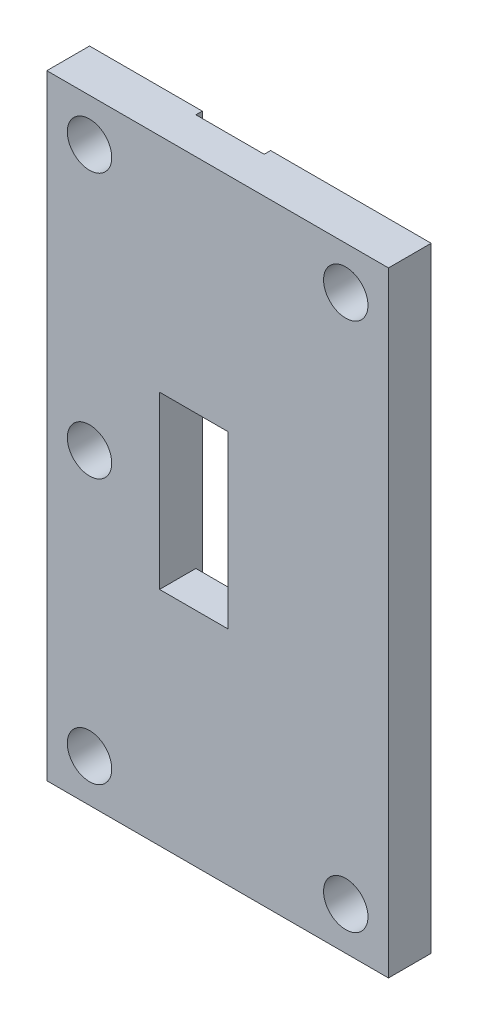
SolidWorks part; units mm, degrees
ref_plane "Front Plane" through (0, 0, 0) normal (0, 0, 1) x (1, 0, 0)
ref_plane "Top Plane" through (0, 0, 0) normal (0, 1, 0) x (1, 0, 0)
ref_plane "Right Plane" through (0, 0, 0) normal (1, 0, 0) x (0, 0, -1)
sketch "Sketch1" plane through (0, 0, 0) normal (0, 1, 0) x (1, 0, 0)
  line L1 (0, 0) -> (40, 0)
  line L2 (0, 0) -> (0, 5)
  line L3 (0, 5) -> (40, 5)
  line L4 (40, 0) -> (40, 5)
  dimension "D1" = 40
  dimension "D2" = 5
  dimension "D3" = 0
extrude "Boss-Extrude1" add sketch "Sketch1" along normal blind 72
sketch "Sketch2" plane through (0, 0, -5) normal (0, 0, -1) x (-1, 0, 0)
  line L0 (-40, 72) -> (0, 72) construction
  line L1 (-13.2, 72) -> (-21.2, 72)
  line L2 (-13.2, 72) -> (-13.2, 0)
  line L3 (-13.2, 0) -> (-21.2, 0)
  line L4 (-21.2, 72) -> (-21.2, 0)
  line L5 (-40, 0) -> (0, 0) construction
  line L7 (-40, 72) -> (-40, 0) construction
  dimension "D1" = 8
  dimension "D2" = 18.8
extrude "Cut-Extrude1" cut sketch "Sketch2" against normal blind 0.75
sketch "Sketch3" plane through (13.2, 0, 0) normal (1, 0, 0) x (0, 0, -1)
  line L1 (4.25, 71.4) -> (4.85, 71.4)
  line L2 (4.25, 71.4) -> (4.25, 70.8)
  line L3 (4.25, 70.8) -> (4.85, 70.8)
  line L4 (4.85, 71.4) -> (4.85, 70.8)
  line L5 (4.25, 69.4) -> (4.85, 69.4)
  line L6 (4.25, 69.4) -> (4.25, 68.8)
  line L7 (4.25, 68.8) -> (4.85, 68.8)
  line L8 (4.85, 69.4) -> (4.85, 68.8)
  line L9 (4.25, 67.4) -> (4.85, 67.4)
  line L10 (4.25, 67.4) -> (4.25, 66.8)
  line L11 (4.25, 66.8) -> (4.85, 66.8)
  line L12 (4.85, 67.4) -> (4.85, 66.8)
  line L13 (4.25, 65.4) -> (4.85, 65.4)
  line L14 (4.25, 65.4) -> (4.25, 64.8)
  line L15 (4.25, 64.8) -> (4.85, 64.8)
  line L16 (4.85, 65.4) -> (4.85, 64.8)
  line L17 (4.25, 63.4) -> (4.85, 63.4)
  line L18 (4.25, 63.4) -> (4.25, 62.8)
  line L19 (4.25, 62.8) -> (4.85, 62.8)
  line L20 (4.85, 63.4) -> (4.85, 62.8)
  line L21 (4.25, 61.4) -> (4.85, 61.4)
  line L22 (4.25, 61.4) -> (4.25, 60.8)
  line L23 (4.25, 60.8) -> (4.85, 60.8)
  line L24 (4.85, 61.4) -> (4.85, 60.8)
  line L25 (4.25, 59.4) -> (4.85, 59.4)
  line L26 (4.25, 59.4) -> (4.25, 58.8)
  line L27 (4.25, 58.8) -> (4.85, 58.8)
  line L28 (4.85, 59.4) -> (4.85, 58.8)
  line L29 (4.25, 57.4) -> (4.85, 57.4)
  line L30 (4.25, 57.4) -> (4.25, 56.8)
  line L31 (4.25, 56.8) -> (4.85, 56.8)
  line L32 (4.85, 57.4) -> (4.85, 56.8)
  line L33 (4.25, 55.4) -> (4.85, 55.4)
  line L34 (4.25, 55.4) -> (4.25, 54.8)
  line L35 (4.25, 54.8) -> (4.85, 54.8)
  line L36 (4.85, 55.4) -> (4.85, 54.8)
  line L37 (4.25, 53.4) -> (4.85, 53.4)
  line L38 (4.25, 53.4) -> (4.25, 52.8)
  line L39 (4.25, 52.8) -> (4.85, 52.8)
  line L40 (4.85, 53.4) -> (4.85, 52.8)
  line L41 (4.25, 51.4) -> (4.85, 51.4)
  line L42 (4.25, 51.4) -> (4.25, 50.8)
  line L43 (4.25, 50.8) -> (4.85, 50.8)
  line L44 (4.85, 51.4) -> (4.85, 50.8)
  line L45 (4.25, 49.4) -> (4.85, 49.4)
  line L46 (4.25, 49.4) -> (4.25, 48.8)
  line L47 (4.25, 48.8) -> (4.85, 48.8)
  line L48 (4.85, 49.4) -> (4.85, 48.8)
  line L49 (4.25, 47.4) -> (4.85, 47.4)
  line L50 (4.25, 47.4) -> (4.25, 46.8)
  line L51 (4.25, 46.8) -> (4.85, 46.8)
  line L52 (4.85, 47.4) -> (4.85, 46.8)
  line L53 (4.25, 45.4) -> (4.85, 45.4)
  line L54 (4.25, 45.4) -> (4.25, 44.8)
  line L55 (4.25, 44.8) -> (4.85, 44.8)
  line L56 (4.85, 45.4) -> (4.85, 44.8)
  line L57 (4.25, 43.4) -> (4.85, 43.4)
  line L58 (4.25, 43.4) -> (4.25, 42.8)
  line L59 (4.25, 42.8) -> (4.85, 42.8)
  line L60 (4.85, 43.4) -> (4.85, 42.8)
  line L61 (4.25, 41.4) -> (4.85, 41.4)
  line L62 (4.25, 41.4) -> (4.25, 40.8)
  line L63 (4.25, 40.8) -> (4.85, 40.8)
  line L64 (4.85, 41.4) -> (4.85, 40.8)
  line L65 (4.25, 39.4) -> (4.85, 39.4)
  line L66 (4.25, 39.4) -> (4.25, 38.8)
  line L67 (4.25, 38.8) -> (4.85, 38.8)
  line L68 (4.85, 39.4) -> (4.85, 38.8)
  line L69 (4.25, 37.4) -> (4.85, 37.4)
  line L70 (4.25, 37.4) -> (4.25, 36.8)
  line L71 (4.25, 36.8) -> (4.85, 36.8)
  line L72 (4.85, 37.4) -> (4.85, 36.8)
  line L73 (4.25, 35.4) -> (4.85, 35.4)
  line L74 (4.25, 35.4) -> (4.25, 34.8)
  line L75 (4.25, 34.8) -> (4.85, 34.8)
  line L76 (4.85, 35.4) -> (4.85, 34.8)
  line L77 (4.25, 33.4) -> (4.85, 33.4)
  line L78 (4.25, 33.4) -> (4.25, 32.8)
  line L79 (4.25, 32.8) -> (4.85, 32.8)
  line L80 (4.85, 33.4) -> (4.85, 32.8)
  line L81 (4.25, 31.4) -> (4.85, 31.4)
  line L82 (4.25, 31.4) -> (4.25, 30.8)
  line L83 (4.25, 30.8) -> (4.85, 30.8)
  line L84 (4.85, 31.4) -> (4.85, 30.8)
  line L85 (4.25, 29.4) -> (4.85, 29.4)
  line L86 (4.25, 29.4) -> (4.25, 28.8)
  line L87 (4.25, 28.8) -> (4.85, 28.8)
  line L88 (4.85, 29.4) -> (4.85, 28.8)
  line L89 (4.25, 27.4) -> (4.85, 27.4)
  line L90 (4.25, 27.4) -> (4.25, 26.8)
  line L91 (4.25, 26.8) -> (4.85, 26.8)
  line L92 (4.85, 27.4) -> (4.85, 26.8)
  line L93 (4.25, 25.4) -> (4.85, 25.4)
  line L94 (4.25, 25.4) -> (4.25, 24.8)
  line L95 (4.25, 24.8) -> (4.85, 24.8)
  line L96 (4.85, 25.4) -> (4.85, 24.8)
  line L97 (4.25, 23.4) -> (4.85, 23.4)
  line L98 (4.25, 23.4) -> (4.25, 22.8)
  line L99 (4.25, 22.8) -> (4.85, 22.8)
  line L100 (4.85, 23.4) -> (4.85, 22.8)
  line L101 (4.25, 21.4) -> (4.85, 21.4)
  line L102 (4.25, 21.4) -> (4.25, 20.8)
  line L103 (4.25, 20.8) -> (4.85, 20.8)
  line L104 (4.85, 21.4) -> (4.85, 20.8)
  line L105 (4.25, 19.4) -> (4.85, 19.4)
  line L106 (4.25, 19.4) -> (4.25, 18.8)
  line L107 (4.25, 18.8) -> (4.85, 18.8)
  line L108 (4.85, 19.4) -> (4.85, 18.8)
  line L109 (4.25, 17.4) -> (4.85, 17.4)
  line L110 (4.25, 17.4) -> (4.25, 16.8)
  line L111 (4.25, 16.8) -> (4.85, 16.8)
  line L112 (4.85, 17.4) -> (4.85, 16.8)
  line L113 (4.25, 15.4) -> (4.85, 15.4)
  line L114 (4.25, 15.4) -> (4.25, 14.8)
  line L115 (4.25, 14.8) -> (4.85, 14.8)
  line L116 (4.85, 15.4) -> (4.85, 14.8)
  line L117 (4.25, 13.4) -> (4.85, 13.4)
  line L118 (4.25, 13.4) -> (4.25, 12.8)
  line L119 (4.25, 12.8) -> (4.85, 12.8)
  line L120 (4.85, 13.4) -> (4.85, 12.8)
  line L121 (4.25, 11.4) -> (4.85, 11.4)
  line L122 (4.25, 11.4) -> (4.25, 10.8)
  line L123 (4.25, 10.8) -> (4.85, 10.8)
  line L124 (4.85, 11.4) -> (4.85, 10.8)
  line L125 (4.25, 9.4) -> (4.85, 9.4)
  line L126 (4.25, 9.4) -> (4.25, 8.8)
  line L127 (4.25, 8.8) -> (4.85, 8.8)
  line L128 (4.85, 9.4) -> (4.85, 8.8)
  line L129 (4.25, 7.4) -> (4.85, 7.4)
  line L130 (4.25, 7.4) -> (4.25, 6.8)
  line L131 (4.25, 6.8) -> (4.85, 6.8)
  line L132 (4.85, 7.4) -> (4.85, 6.8)
  line L133 (4.25, 5.4) -> (4.85, 5.4)
  line L134 (4.25, 5.4) -> (4.25, 4.8)
  line L135 (4.25, 4.8) -> (4.85, 4.8)
  line L136 (4.85, 5.4) -> (4.85, 4.8)
  line L137 (4.25, 3.4) -> (4.85, 3.4)
  line L138 (4.25, 3.4) -> (4.25, 2.8)
  line L139 (4.25, 2.8) -> (4.85, 2.8)
  line L140 (4.85, 3.4) -> (4.85, 2.8)
  line L141 (4.25, 1.4) -> (4.85, 1.4)
  line L142 (4.25, 1.4) -> (4.25, 0.8)
  line L143 (4.25, 0.8) -> (4.85, 0.8)
  line L144 (4.85, 1.4) -> (4.85, 0.8)
  line L146 (0, 72) -> (5, 72) construction
  line L147 (4.25, 0) -> (4.25, 72) construction
  dimension "D1" = 0.6
  dimension "D3" = 0.6
  dimension "D4" = 0.6
  dimension "D5" = 0
  dimension "D2" = 36
extrude "Boss-Extrude2" add sketch "Sketch3" along normal blind 8
sketch "Sketch4" plane through (0, 0, 0) normal (0, 0, 1) x (1, 0, 0)
  line L0 (0, 72) -> (40, 72) construction
  line L1 (0, 72) -> (0, 0) construction
  line L2 (40, 72) -> (40, 0) construction
  line L3 (0, 0) -> (40, 0) construction
  circle A0 centre (5, 67) radius 2.6
  circle A1 centre (35, 67) radius 2.6
  circle A2 centre (5, 5) radius 2.6
  circle A3 centre (35, 5) radius 2.6
  circle A4 centre (5, 36) radius 2.6
  dimension "D1" = 5.2
  dimension "D4" = 5.2
  dimension "D7" = 5.2
  dimension "D10" = 5.2
  dimension "D13" = 5.2
  dimension "D2" = 5
  dimension "D3" = 5
  dimension "D5" = 5
  dimension "D6" = 5
  dimension "D8" = 5
  dimension "D9" = 5
  dimension "D11" = 5
  dimension "D12" = 5
  dimension "D14" = 5
  dimension "D15" = 36
extrude "Cut-Extrude2" cut sketch "Sketch4" against normal through all
sketch "Sketch5" plane through (0, 0, 0) normal (0, 0, 1) x (1, 0, 0)
  line L1 (21.2, 46) -> (13.2, 46)
  line L2 (21.2, 46) -> (21.2, 26)
  line L3 (21.2, 26) -> (13.2, 26)
  line L4 (13.2, 46) -> (13.2, 26)
  line L5 (0, 72) -> (40, 72) construction
  line L7 (0, 72) -> (0, 0) construction
  dimension "D1" = 8
  dimension "D2" = 20
  dimension "D3" = 26
  dimension "D4" = 13.2
extrude "Cut-Extrude3" cut sketch "Sketch5" against normal through all
equation "\"D4@Sketch4\"=\"D1@Sketch4\""
equation "\"D5@Sketch4\"=\"D3@Sketch4\""
equation "\"D6@Sketch4\"=\"D3@Sketch4\""
equation "\"D2@Sketch4\"=\"D3@Sketch4\""
equation "\"D7@Sketch4\"=\"D1@Sketch4\""
equation "\"D8@Sketch4\"=\"D3@Sketch4\""
equation "\"D9@Sketch4\"=\"D3@Sketch4\""
equation "\"D10@Sketch4\"=\"D1@Sketch4\""
equation "\"D11@Sketch4\"=\"D3@Sketch4\""
equation "\"D12@Sketch4\"=\"D3@Sketch4\""
equation "\"D13@Sketch4\"=\"D1@Sketch4\""
equation "\"D14@Sketch4\"=\"D3@Sketch4\""
